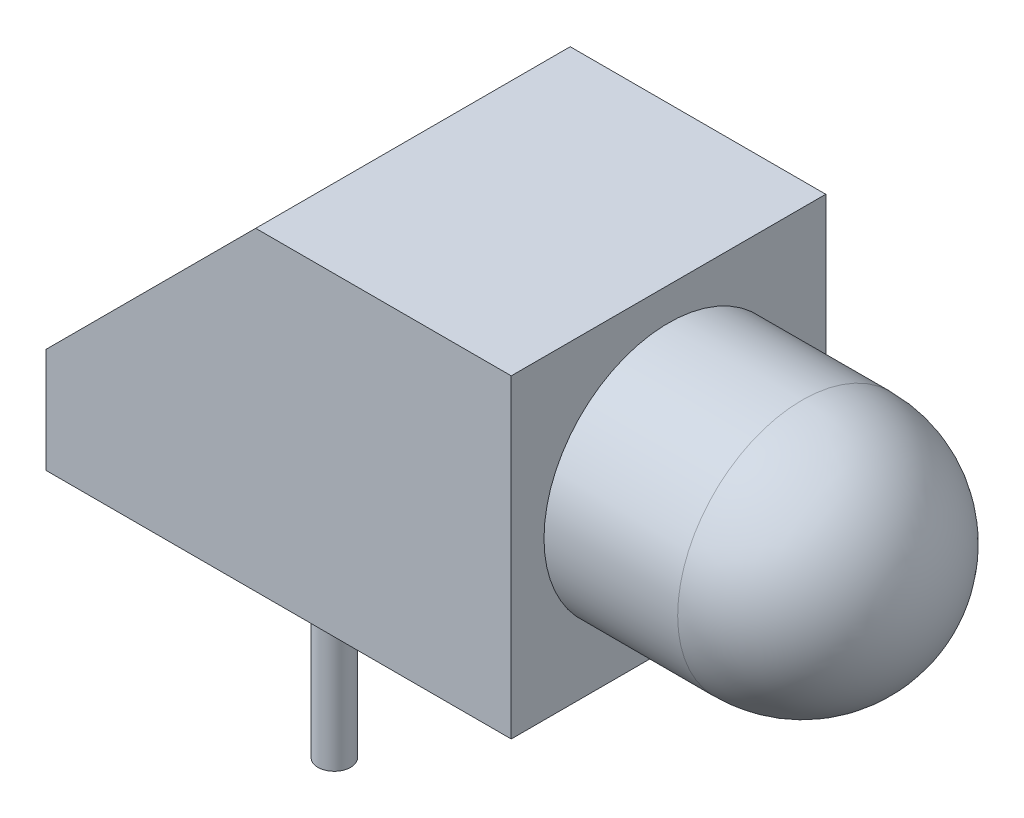
SolidWorks part; units mm, degrees
ref_plane "front" through (0, 0, 0) normal (0, 0, 1) x (1, 0, 0)
ref_plane "top" through (0, 0, 0) normal (0, 1, 0) x (1, 0, 0)
ref_plane "right" through (0, 0, 0) normal (1, 0, 0) x (0, 0, -1)
sketch "Sketch1" plane through (0, 0, 0) normal (0, 0, 1) x (1, 0, 0)
  line L0 (0, 0) -> (0, 6.096)
  line L1 (0, 6.096) -> (-4.953, 6.096)
  line L2 (-4.953, 6.096) -> (-9.017, 2.032)
  line L3 (-9.017, 2.032) -> (-9.017, 0)
  line L4 (-9.017, 0) -> (0, 0)
  dimension "D1" = 45
  dimension "D2" = 4.064
  dimension "D3" = 9.017
  dimension "D4" = 6.096
extrude "Extrude1" add sketch "Sketch1" along normal mid plane 6.096
sketch "Sketch2" plane through (0, 0, 0) normal (0, 0, 1) x (1, 0, 0)
  line L0 (-1.016, 3.048) -> (5.0038, 3.048)
  line L1 (-1.016, 5.461) -> (2.5908, 5.461)
  line L2 (5.0038, 3.048) -> (10.0922, 3.048) construction
  line L3 (-1.016, 5.461) -> (-1.016, 3.048)
  arc A0 (2.5908, 5.461) -> (5.0038, 3.048) centre (2.5908, 3.048) cw
  dimension "D1" = 3.048
  dimension "D2" = 4.826
  dimension "D3" = 5.0038
  dimension "D4" = 1.016
revolve "Revolve1" add sketch "Sketch2" angle 360 about L2
sketch "Sketch3" plane through (0, 0, 0) normal (0, 1, 0) x (1, 0, 0)
  circle A0 centre (-5.207, -1.27) radius 0.3175
  circle A1 centre (-5.207, 1.27) radius 0.3175
  dimension "D2" = 0.635
  dimension "D1" = 5.207
  dimension "D3" = 1.27
  dimension "D4" = 1.27
extrude "Extrude2" add sketch "Sketch3" against normal blind 3.81
